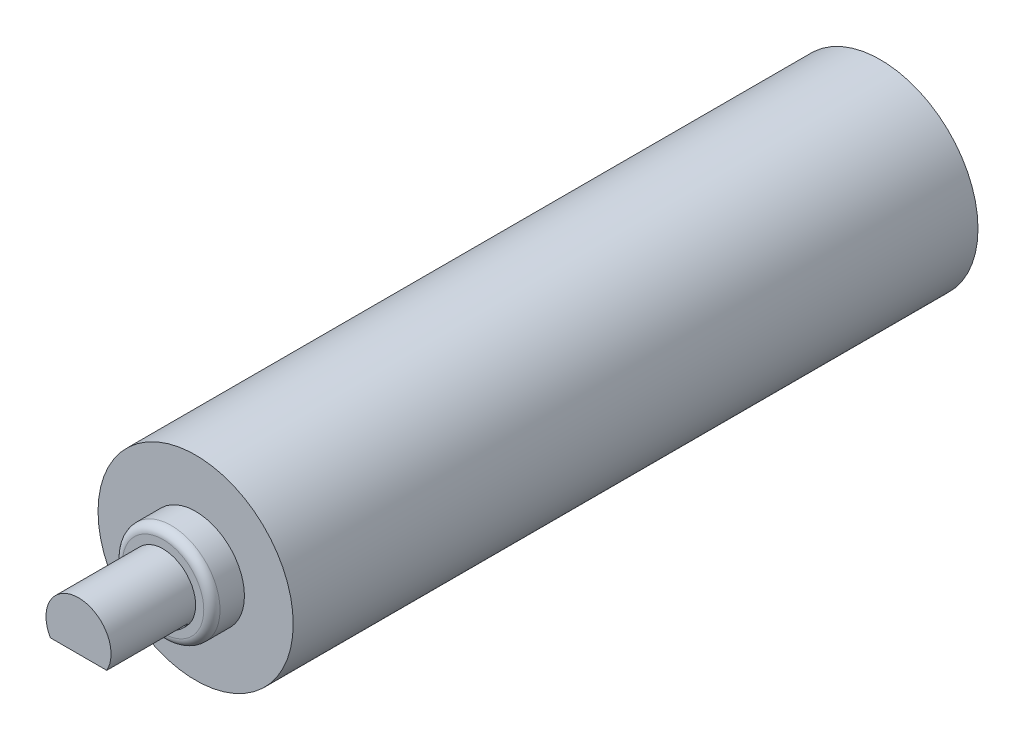
SolidWorks part; units mm, degrees
material "0.7033 (EN-GJS-350-22-LT)"
ref_plane "前视基准面" through (0, 0, 0) normal (0, 0, 1) x (1, 0, 0)
ref_plane "上视基准面" through (0, 0, 0) normal (0, 1, 0) x (1, 0, 0)
ref_plane "右视基准面" through (0, 0, 0) normal (1, 0, 0) x (0, 0, -1)
sketch "草图1" plane through (0, 0, 0) normal (0, 0, 1) x (1, 0, 0)
  circle A0 centre (0, 0) radius 3
  dimension "D1" = 6
extrude "凸台-拉伸1" add sketch "草图1" against normal blind 21.05
sketch "草图2" plane through (0, 0, 0) normal (0, 0, 1) x (1, 0, 0)
  circle A0 centre (0, 0) radius 1.5
  dimension "D1" = 3
extrude "凸台-拉伸2" add sketch "草图2" along normal blind 1
sketch "草图3" plane through (0, 0, 1) normal (0, 0, 1) x (1, 0, 0)
  circle A0 centre (0, 0) radius 1
  dimension "D1" = 2
extrude "凸台-拉伸3" add sketch "草图3" along normal blind 2.6
sketch "草图4" plane through (0, 0, 3.6) normal (0, 0, 1) x (1, 0, 0)
  line L0 (0, 1) -> (0, -0.5) construction
  line L2 (0, -0.5) -> (0.8625, -0.5)
  line L4 (0, -1) -> (0.8625, -1)
  line L5 (0.8625, -0.5) -> (0.8625, -1)
  line L6 (0, -0.5) -> (-0.8694, -0.5)
  line L8 (0, -1) -> (-0.8694, -1)
  line L9 (-0.8694, -0.5) -> (-0.8694, -1)
  circle A0 centre (0, 0) radius 1 construction
  circle A1 centre (0, 0) radius 1 construction
  dimension "D1" = 1.5
extrude "切除-拉伸1" cut sketch "草图4" against normal blind 2.5
fillet "圆角1" radius 0.25 1 edges at (1.5, 0, 1)
